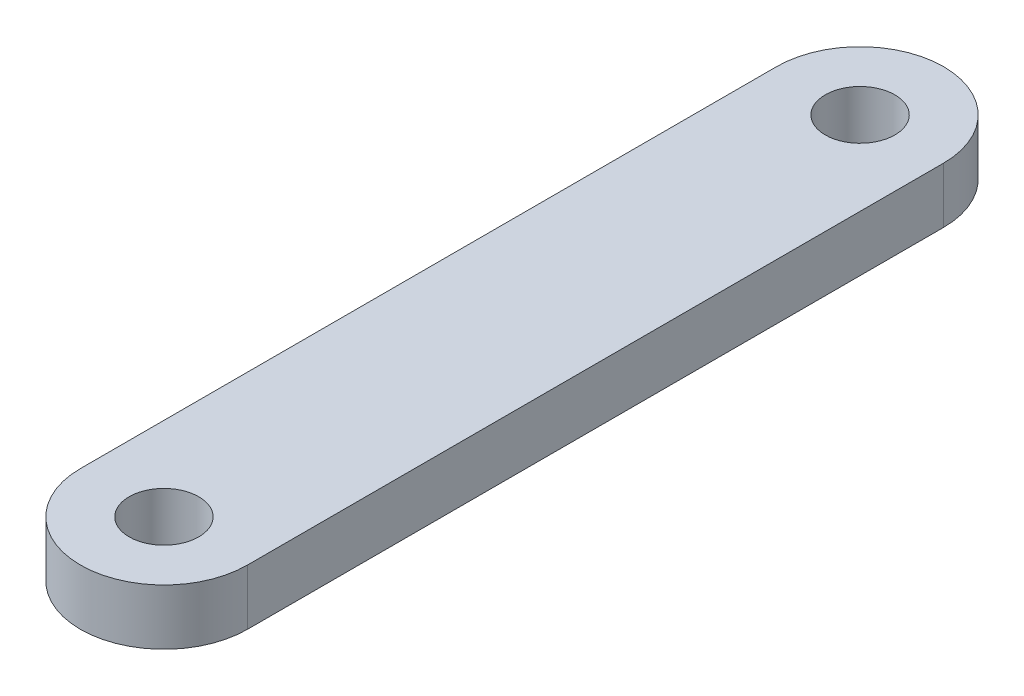
SolidWorks part; units mm, degrees
material "ABS"
ref_plane "正面" through (0, 0, 0) normal (0, 0, 1) x (1, 0, 0)
ref_plane "平面" through (0, 0, 0) normal (0, 1, 0) x (1, 0, 0)
ref_plane "右側面" through (0, 0, 0) normal (1, 0, 0) x (0, 0, -1)
sketch "ｽｹｯﾁ1" plane through (0, 0, 0) normal (0, 1, 0) x (1, 0, 0)
  line L0 (-12, 0) -> (-12, 100)
  line L1 (12, 100) -> (12, 0)
  arc A0 (-12, 100) -> (12, 100) centre (0, 100) cw
  arc A1 (12, 0) -> (-12, 0) centre (0, 0) cw
  circle A2 centre (0, 0) radius 5
  circle A3 centre (0, 100) radius 5
extrude "ﾎﾞｽ - 押し出し1" add sketch "ｽｹｯﾁ1" along normal blind 8
